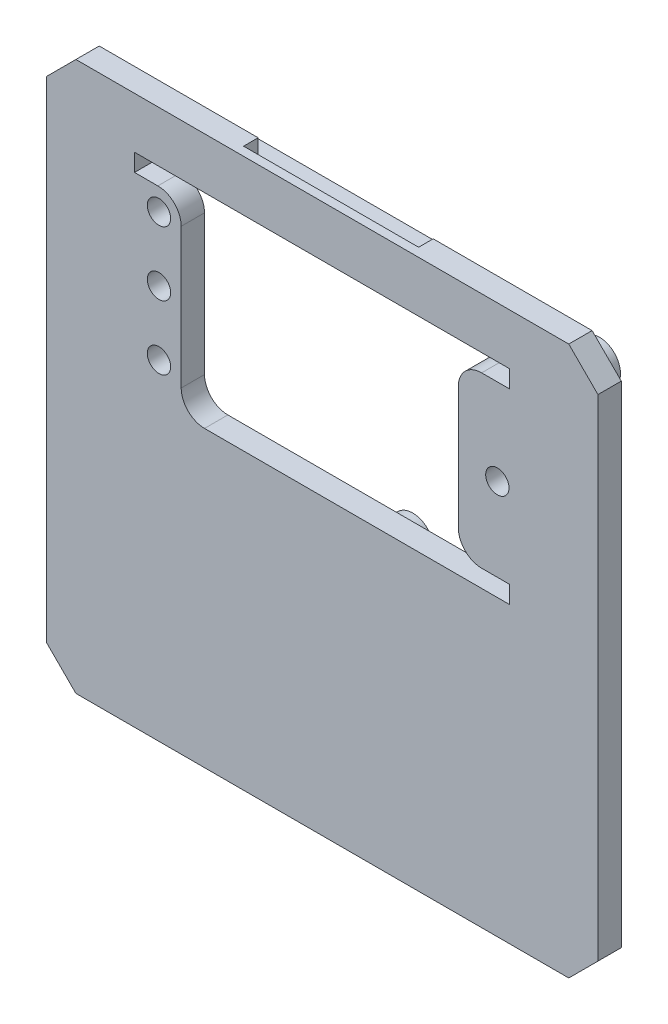
SolidWorks part; units mm, degrees
ref_plane "Front Plane" through (0, 0, 0) normal (0, 0, 1) x (1, 0, 0)
ref_plane "Top Plane" through (0, 0, 0) normal (0, 1, 0) x (1, 0, 0)
ref_plane "Right Plane" through (0, 0, 0) normal (1, 0, 0) x (0, 0, -1)
sketch "Sketch1" plane through (0, 0, 0) normal (0, 0, 1) x (1, 0, 0)
  line L1 (-29.9964, 29.8768) -> (29.9964, 29.8768)
  line L2 (-29.9964, 29.8768) -> (-29.9964, -29.8767)
  line L3 (-29.9964, -29.8767) -> (29.9964, -29.8767)
  line L4 (29.9964, 29.8768) -> (29.9964, -29.8767)
  line L5 (-29.9964, 29.8768) -> (29.9964, -29.8767) construction
  line L6 (-29.9964, -29.8767) -> (29.9964, 29.8768) construction
  point P0 (0, 0)
  dimension "D1" = 59.9928
  dimension "D2" = 59.7535
extrude "Boss-Extrude1" add sketch "Sketch1" along normal blind 2.54
sketch "Sketch2" plane through (0, 0, 0) normal (0, 0, -1) x (-1, 0, 0)
  circle A0 centre (-22.859, 22.6043) radius 2.286
  circle A1 centre (22.861, 21.9393) radius 2.286
  circle A2 centre (22.861, 4.1593) radius 2.286
  circle A3 centre (-22.859, 3.4943) radius 2.286
  circle A4 centre (-22.859, -4.1257) radius 2.286
  circle A5 centre (-2.539, -4.1257) radius 2.286
  circle A6 centre (-22.859, -21.9057) radius 2.286
  circle A7 centre (-2.539, -21.9057) radius 2.286
  dimension "D1" = 4.572
extrude "Boss-Extrude2" add sketch "Sketch2" along normal blind 4.7625
sketch "Sketch3" plane through (0, 0, -4.7625) normal (0, 0, -1) x (-1, 0, 0)
  circle A0 centre (-22.859, 22.6043) radius 1.27
  circle A1 centre (22.861, 21.9393) radius 1.27
  circle A2 centre (22.861, 4.1593) radius 1.27
  circle A3 centre (-2.539, -4.1257) radius 1.27
  circle A4 centre (-22.859, 3.4943) radius 1.27
  circle A5 centre (-22.859, -4.1257) radius 1.27
  circle A6 centre (-22.859, -21.9057) radius 1.27
  circle A7 centre (-2.539, -21.9057) radius 1.27
  dimension "D1" = 2.54
extrude "Cut-Extrude1" cut sketch "Sketch3" against normal blind 3.175
sketch "Sketch4" plane through (0, 0, 2.54) normal (0, 0, 1) x (1, 0, 0)
  line L0 (29.9964, 29.8768) -> (-29.9984, 29.8768) construction
  line L1 (14.8009, 24.3269) -> (-15.3616, 24.3269)
  line L2 (14.8009, 24.3269) -> (14.8009, 2.1019)
  line L3 (14.8009, 2.1019) -> (-15.3616, 2.1019)
  line L4 (-15.3616, 24.3269) -> (-15.3616, 2.1019)
  line L5 (-29.9984, 26.7018) -> (-29.9984, -26.7017) construction
  point P6 (-15.3616, 13.2144)
  point P9 (-0.2804, 24.3269)
  dimension "D1" = 22.225
  dimension "D2" = 30.1625
  dimension "D3" = 16.6624
  dimension "D4" = 29.718
extrude "Cut-Extrude2" cut sketch "Sketch4" against normal up to next
sketch "Sketch5" plane through (0, 0, 2.54) normal (0, 0, 1) x (1, 0, 0)
  circle A0 centre (-17.781, 20.0343) radius 1.27
  circle A1 centre (-17.781, 13.0493) radius 1.27
  circle A2 centre (-17.781, 6.0643) radius 1.27
  circle A3 centre (19.049, 13.0493) radius 1.27
  dimension "D1" = 2.54
extrude "Cut-Extrude3" cut sketch "Sketch5" against normal up to next
sketch "Sketch6" plane through (0, 0, 0) normal (0, 0, -1) x (-1, 0, 0)
  line L0 (0, 25.019) -> (0, 0) construction
  line L1 (-19.05, 26.6065) -> (19.05, 26.6065)
  line L2 (-19.05, 26.6065) -> (-19.05, 25.019)
  line L3 (-19.05, 25.019) -> (19.05, 25.019)
  line L4 (19.05, 26.6065) -> (19.05, 25.019)
  line L5 (-19.05, -25.019) -> (19.05, -25.019)
  line L6 (-19.05, -25.019) -> (-19.05, -26.6065)
  line L7 (-19.05, -26.6065) -> (19.05, -26.6065)
  line L8 (19.05, -25.019) -> (19.05, -26.6065)
  line L9 (0, 0) -> (0, -25.019) construction
  dimension "D1" = 1.5875
  dimension "D2" = 1.5875
  dimension "D3" = 38.1
  dimension "D4" = 38.1
  dimension "D5" = 25.019
  dimension "D6" = 25.019
extrude "Boss-Extrude3" add sketch "Sketch6" along normal blind 3.175
chamfer "Chamfer1" distance 3.175 angle 45 4 edges at (29.9964, -29.8767, 1.27) (-29.9964, -29.8767, 1.27) (-29.9964, 29.8768, 1.27) (29.9964, 29.8768, 1.27)
sketch "Sketch7" plane through (0, 0, 0) normal (1, 0, 0) x (0, 0, -1)
  line L0 (3.175, 26.6065) -> (0, 26.6065) construction
  line L1 (3.175, -26.6065) -> (0, -26.6065) construction
  line L2 (0, 26.6065) -> (0.5, 26.6065)
  line L3 (0, -26.6065) -> (0.5, -26.6065)
  arc A0 (0, 26.6065) -> (0.5, 26.6065) centre (0.25, 26.6065) ccw
  arc A1 (0, -26.6065) -> (0.5, -26.6065) centre (0.25, -26.6065) cw
  point P16 (0.25, 26.6065)
  dimension "D1" = 0.5
extrude "Cut-Extrude4" cut sketch "Sketch7" against normal through all both and the other way through all
sketch "Sketch8" plane through (0, 0, 0) normal (1, 0, 0) x (0, 0, -1)
  line L0 (-2.54, 29.8768) -> (0, 29.8768) construction
  line L1 (0, 29.8768) -> (0, 26.7018) construction
  circle A0 centre (0, 29.8768) radius 1.5875
  circle A1 centre (0, -29.8767) radius 1.5875
  dimension "D1" = 3.175
  dimension "D2" = 3.175
extrude "Cut-Extrude5" cut sketch "Sketch8" against normal blind 9.525 and the other way blind 9.525
sketch "Sketch9" plane through (0, 0, 2.54) normal (0, 0, 1) x (1, 0, 0)
  line L1 (14.8009, 2.1019) -> (20.3889, 2.1019)
  line L2 (14.8009, 2.1019) -> (14.8009, 4.0069)
  line L3 (14.8009, 4.0069) -> (20.3889, 4.0069)
  line L4 (20.3889, 2.1019) -> (20.3889, 4.0069)
  line L5 (-15.3616, 24.3269) -> (-20.4416, 24.3269)
  line L6 (-15.3616, 24.3269) -> (-15.3616, 22.4219)
  line L7 (-15.3616, 22.4219) -> (-20.4416, 22.4219)
  line L8 (-20.4416, 24.3269) -> (-20.4416, 22.4219)
  line L9 (14.8009, 24.3269) -> (20.3889, 24.3269)
  line L10 (14.8009, 24.3269) -> (14.8009, 22.4219)
  line L11 (14.8009, 22.4219) -> (20.3889, 22.4219)
  line L12 (20.3889, 24.3269) -> (20.3889, 22.4219)
  dimension "D1" = 5.588
  dimension "D2" = 5.08
  dimension "D3" = 5.588
  dimension "D4" = 1.905
  dimension "D5" = 1.905
  dimension "D6" = 1.905
extrude "Cut-Extrude6" cut sketch "Sketch9" against normal through all
fillet "Fillet1" radius 2.54 4 edges at (-15.3616, 22.4219, 1.27) (14.8009, 22.4219, 1.27) (14.8009, 4.0069, 1.27) (-15.3616, 2.1019, 1.27)
